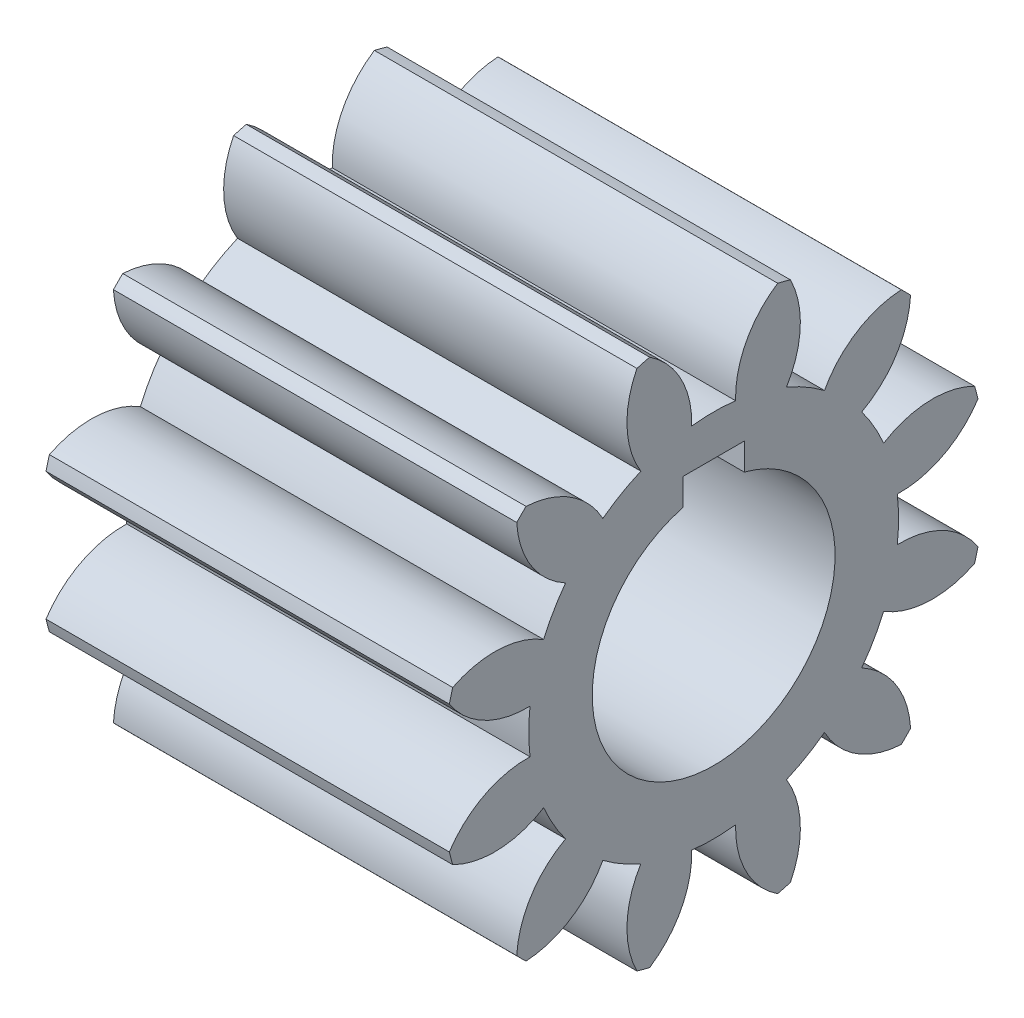
SolidWorks part; units mm, degrees
material "6061 Alloy"
ref_plane "Plane1" through (0, 0, 0) normal (0, 0, 1) x (1, 0, 0)
ref_plane "Plane2" through (0, 0, 0) normal (0, 1, 0) x (1, 0, 0)
ref_plane "Plane3" through (0, 0, 0) normal (1, 0, 0) x (0, 0, -1)
sketch "HoldingSke" plane through (0, 0, 0) normal (0, 1, 0) x (1, 0, 0)
  line L0 (0, 0) -> (496.899, -105.6191)
  line L1 (-15, 0) -> (100, 0) construction
  line L2 (0, 0) -> (-2.1039, 2.3779)
  line L3 (0, 0) -> (-11.863, 4.5341)
  line L4 (0, 0) -> (8.4473, 1.7955)
  line L5 (0, 0) -> (-9.5432, -3.5593)
  line L6 (0, 0) -> (-10.9279, -7.3731)
  line L7 (-2.1039, 2.3779) -> (0.7337, 15.2515)
  line L8 (-76.2, 54.61) -> (-67.9958, 54.61)
  line L9 (-71.009, 38.7566) -> (-53.1078, 45.2721)
  line L10 (-76.2, 71.12) -> (104.1128, 71.12)
  line L11 (0, 0) -> (-13.1826, 0)
  line L12 (-76.2, 101.6) -> (-76.1492, 101.6)
  line L13 (24.9733, 27.94) -> (52.9518, 28.4284)
  line L14 (24.9733, 27.94) -> (25.0241, 27.9398)
  line L15 (24.9733, 27.94) -> (100.4021, 29.52)
  circle A0 centre (0, 0) radius 3.9688
  circle A1 centre (0, 0) radius 6.0452
  circle A2 centre (0, 0) radius 8.9281
  circle A3 centre (0, 0) radius 3.9688
  dimension "MHD" = 12.0904
  dimension "Hub_dia" = 17.8562
  dimension "Bore" = 7.9375
  dimension "MBD" = 7.9375
  dimension "Num_teeth" = 12
  dimension "Pitch_radius" = 180.3128
  dimension "Pitch" = 508
  dimension "Width" = 13.1826
  dimension "Overall_len" = 10.1854
  dimension "Show_teeth" = 12
  dimension "Thickness" = 13.1826
  dimension "OAL" = 13.1827
  dimension "T_dim" = 8.2042
  dimension "Ap" = 20
  dimension "H" = 19.05
  dimension "Backlash" = 0.0508
  dimension "Addendum_fac" = 1
  dimension "Dedendum_fac" = 1.2
  dimension "Clearance_fac" = 0.2
  dimension "Dedendum_add" = 0.0508
sketch "BasProSke" plane through (0, 0, 0) normal (0, 1, 0) x (1, 0, 0)
  line L0 (-10, 0) -> (60, 0) construction
  line L1 (0, 0) -> (0, 8.89)
  line L2 (0, 0) -> (13.1826, 0)
  line L3 (13.1826, 0) -> (13.1826, 8.89)
  line L4 (13.1826, 8.89) -> (0, 8.89)
  dimension "Diameter" = 17.78
  dimension "Thickness" = 13.1826
revolve "Base-Revolve" add sketch "BasProSke" angle 360 about L0
sketch "TooCutSke" plane through (0, 0, 0) normal (1, 0, 0) x (0, 0, -1)
  line L1 (0, 0) -> (0, 107) construction
  line L2 (0, 0) -> (-1.0834, 7.5426) construction
  line L3 (0, 0) -> (-3.9164, 14.6164) construction
  line L4 (-1.0834, 7.5426) -> (-1.9582, 7.3082) construction
  arc A0 (0.7171, 6.0025) -> (-0.7171, 6.0025) centre (0, 0) ccw
  arc A1 (2.1216, 8.6593) -> (-2.1216, 8.6593) centre (0, 0) ccw
  circle A2 centre (0, 0) radius 7.62 construction
  circle A3 centre (0, 0) radius 7.1605 construction
  arc A4 (-0.7171, 6.0025) -> (-2.1216, 8.6593) centre (-3.7638, 6.0915) ccw
  arc A5 (2.1216, 8.6593) -> (0.7171, 6.0025) centre (3.7638, 6.0915) ccw
  dimension "Root_dia" = 12.0904
  dimension "Overcut_dia" = 17.8308
  dimension "Pitch_dia" = 15.24
  dimension "Base_dia" = 14.3209
  dimension "Flank_rad" = 3.048
  dimension "Half_ang" = 15
  dimension "Half_CT" = 0.9057
extrude "ToothCut" cut sketch "TooCutSke" along normal through all
fillet "Breaks" [suppressed] radius 0.0254
fillet "RootFillets" [suppressed] radius 0.3048
pattern_circular "TeethCuts" count 12 every 30 about axis through (-10, 0, 0) along (1, 0, 0) of "ToothCut", "RootFillets", "Breaks"
sketch "HubNeaOneSke" plane through (0, 0, 0) normal (-1, 0, 0) x (0, 0, 1)
  circle A0 centre (0, 0) radius 6.0452
  dimension "Diameter" = 12.0904
extrude "HubNearOne" [suppressed] add sketch "HubNeaOneSke" along normal blind 38.1001
sketch "HubNeaBotSke" plane through (0, 0, 0) normal (-1, 0, 0) x (0, 0, 1)
  circle A0 centre (0, 0) radius 6.0452
  dimension "Diameter" = 12.0904
extrude "HubNearBoth" [suppressed] add sketch "HubNeaBotSke" along normal blind 19.05
ref_plane "FarPln" through (13.1826, 0, 0) normal (1, 0, 0) x (0, 0, -1)
sketch "HubFarSke" plane through (13.1826, 0, 0) normal (1, 0, 0) x (0, 0, -1)
  circle A0 centre (0, 0) radius 6.0452
  dimension "Diameter" = 12.0904
extrude "HubFar" [suppressed] add sketch "HubFarSke" along normal blind 19.05
sketch "BorSke" plane through (0, 0, 0) normal (1, 0, 0) x (0, 0, -1)
  circle A0 centre (0, 0) radius 3.9688
  dimension "Diameter" = 7.9375
extrude "Bore" cut sketch "BorSke" along normal mid plane 26.3653
sketch "KeySke" plane through (0, 0, 0) normal (1, 0, 0) x (0, 0, -1)
  line L0 (-0.127, 0) -> (-0.127, 4.2355)
  line L1 (-0.127, 4.2355) -> (0.127, 4.2355)
  line L2 (0.127, 4.2355) -> (0.127, 0)
  line L3 (0, 0) -> (0, 34) construction
  line L4 (-0.127, 0) -> (0.127, 0)
  dimension "Offset" = 4.2355
  dimension "Width" = 0.254
extrude "Keyway" [suppressed] cut sketch "KeySke" along normal mid plane 26.3653
pattern_circular "Keyway2" [suppressed] count 2 every 90 about axis through (-10, 0, 0) along (1, 0, 0)
sketch "Sketch1" plane through (13.1826, 0, 0) normal (1, 0, 0) x (0, 0, -1)
  line L0 (-1, 3.8407) -> (-1, 4.7188)
  line L1 (-1, 4.7188) -> (1, 4.7188)
  line L2 (1, 4.7188) -> (1, 3.8407)
  line L3 (0, -1000) -> (0, 49000) construction
  circle A0 centre (0, 0) radius 3.9688 construction
  arc A1 (1, 3.8407) -> (-1, 3.8407) centre (0, 0) ccw
  point P6 (0, 4.7188)
  dimension "D1" = 2
  dimension "D2" = 0.75
extrude "Cut-Extrude1" cut sketch "Sketch1" against normal through all
equation "' \"Pitch@HoldingSke\" = 4"
equation "' \"Num_teeth@HoldingSke\" = 12"
equation "' \"Ap@HoldingSke\" =  20"
equation "' \"Width@HoldingSke\" = 0.5"
equation "' \"Hub_dia@HoldingSke\"= 1"
equation "' \"Overall_len@HoldingSke\" = 1.0"
equation "' \"Bore@HoldingSke\" = 0.75"
equation "' \"T_dim@HoldingSke\" = 0.85"
equation "' \"Width@KeySke\" = 0.25"
equation "' \"Show_teeth@HoldingSke\" = 13"
equation "' \"Backlash@HoldingSke\" = 0.009"
equation "' \"Addendum_fac@HoldingSke\" = 1.0"
equation "' \"Dedendum_fac@HoldingSke\" = 1.25"
equation "' \"Dedendum_add@HoldingSke\" = 0.00005"
equation "' \"Clearance_fac@HoldingSke\" = 0.25"
equation "' \"Pitch@HoldingSke\" = 0.5"
equation "' \"Num_teeth@HoldingSke\" = 23"
equation "' \"Show_teeth@HoldingSke\" = 23"
equation "' \"Backlash@HoldingSke\" = 0.0375"
equation "\"Overcut_dia@TooCutSke\" = (\"Num_teeth@HoldingSke\" + 2 * \"Addendum_fac@HoldingSke\") / \"Pitch@HoldingSke\" + 0.002"
equation "\"Pitch_dia@TooCutSke\" = \"Num_teeth@HoldingSke\" / \"Pitch@HoldingSke\""
equation "\"Base_dia@TooCutSke\" = \"Num_teeth@HoldingSke\" / \"Pitch@HoldingSke\" * cos((\"Ap@HoldingSke\"  * 3.14159265 / 180))"
equation "\"Root_dia@TooCutSke\" = (\"Num_teeth@HoldingSke\" + 2) / \"Pitch@HoldingSke\" - 2 * (\"Addendum_fac@HoldingSke\" + \"Dedendum_fac@HoldingSke\") / \"Pitch@HoldingSke\" - \"Dedendum_add@HoldingSke\" * 2"
equation "\"Half_ang@TooCutSke\" = 180 / \"Num_teeth@HoldingSke\""
equation "\"Half_CT@TooCutSke\" = \"Num_teeth@HoldingSke\" / \"Pitch@HoldingSke\" * sin((3.14159265 / 2 / \"Num_teeth@HoldingSke\")) / 2 - 7 * \"Backlash@HoldingSke\" / 4"
equation "\"Flank_rad@TooCutSke\" = \"Num_teeth@HoldingSke\" / \"Pitch@HoldingSke\" / 5"
equation "\"Radius@RootFillets\" = \"Clearance_fac@HoldingSke\" / \"Pitch@HoldingSke\" + \"Dedendum_add@HoldingSke\""
equation "\"Break_rad@Breaks\" = 0.02 / \"Pitch@HoldingSke\""
equation "\"Thickness@HoldingSke\" = \"Width@HoldingSke\""
equation "\"OAL@HoldingSke\" = \"Thickness@HoldingSke\""
equation "\"MHD@HoldingSke\" = (\"Num_teeth@HoldingSke\" + 2) / \"Pitch@HoldingSke\" - 2 * (\"Addendum_fac@HoldingSke\" + \"Dedendum_fac@HoldingSke\")  / \"Pitch@HoldingSke\" - \"Dedendum_add@HoldingSke\" * 2"
equation "\"MBD@HoldingSke\" = (\"Num_teeth@HoldingSke\" + 2) / \"Pitch@HoldingSke\" - 2 * (\"Addendum_fac@HoldingSke\" + \"Dedendum_fac@HoldingSke\")  / \"Pitch@HoldingSke\" - \"Dedendum_add@HoldingSke\" * 2 - 0.002"
equation "\"MHD@HoldingSke\" = ((sgn( \"MHD@HoldingSke\" - \"Hub_dia@HoldingSke\" )-1)*( \"MHD@HoldingSke\" - \"Hub_dia@HoldingSke\" ))/-2+ \"Hub_dia@HoldingSke\""
equation "\"MBD@HoldingSke\" = ((sgn( \"MBD@HoldingSke\" - \"Bore@HoldingSke\" )-1)*( \"MBD@HoldingSke\" - \"Bore@HoldingSke\" ))/-2+ \"Bore@HoldingSke\""
equation "\"OAL@HoldingSke\" = ((sgn( \"OAL@HoldingSke\" - \"Overall_len@HoldingSke\" )+1)*( \"OAL@HoldingSke\" - \"Overall_len@HoldingSke\" ))/2 + \"Overall_len@HoldingSke\" + 0.000002"
equation "\"Num_teeth@TeethCuts\" = int( \"Show_teeth@HoldingSke\" ) + 1"
equation "\"Num_teeth@TeethCuts\" = ((sgn( \"Num_teeth@TeethCuts\" - \"Num_teeth@HoldingSke\" )-1)*( \"Num_teeth@TeethCuts\" - \"Num_teeth@HoldingSke\" ))/-2+ \"Num_teeth@HoldingSke\""
equation "\"Num_teeth@TeethCuts\" = ((sgn( \"Num_teeth@TeethCuts\" - 2.0)+1)*( \"Num_teeth@TeethCuts\" - 2.0))/2 +2.0"
equation "\"Angle@TeethCuts\" = 360.0 / \"Num_teeth@HoldingSke\""
equation "\"Diameter@BasProSke\" = (\"Num_teeth@HoldingSke\" + 2 * \"Addendum_fac@HoldingSke\") / \"Pitch@HoldingSke\""
equation "\"Thickness@BasProSke\"  = \"Thickness@HoldingSke\""
equation "' \"Fillet_rad@BasProSke\" =  \"Thickness@HoldingSke\" * 0.05"
equation "\"MHD@HoldingSke\" = ((sgn( \"MHD@HoldingSke\" - \"Root_dia@TooCutSke\" )-1)*( \"MHD@HoldingSke\" - \"Root_dia@TooCutSke\" ))/-2+ \"Root_dia@TooCutSke\""
equation "\"Diameter@HubNeaOneSke\" = \"MHD@HoldingSke\""
equation "\"Length@HubNearOne\" = \"OAL@HoldingSke\" - \"Thickness@BasProSke\""
equation "\"Diameter@HubNeaBotSke\" = \"MHD@HoldingSke\""
equation "\"Length@HubNearBoth\" = ( \"OAL@HoldingSke\" - \"Thickness@BasProSke\" ) / 2.0"
equation "\"Thickness@FarPln\" = \"Thickness@BasProSke\""
equation "\"Diameter@HubFarSke\" = \"MHD@HoldingSke\""
equation "\"Length@HubFar\" = ( \"OAL@HoldingSke\" - \"Thickness@BasProSke\" ) / 2.0"
equation "\"Diameter@BorSke\" = \"MBD@HoldingSke\""
equation "\"D1@Bore\" = \"OAL@HoldingSke\" * 2.0"
equation "\"D1@Keyway\" = \"OAL@HoldingSke\" * 2.0"
equation "\"Offset@KeySke\" = \"T_dim@HoldingSke\" - \"MBD@HoldingSke\" / 2.0"
